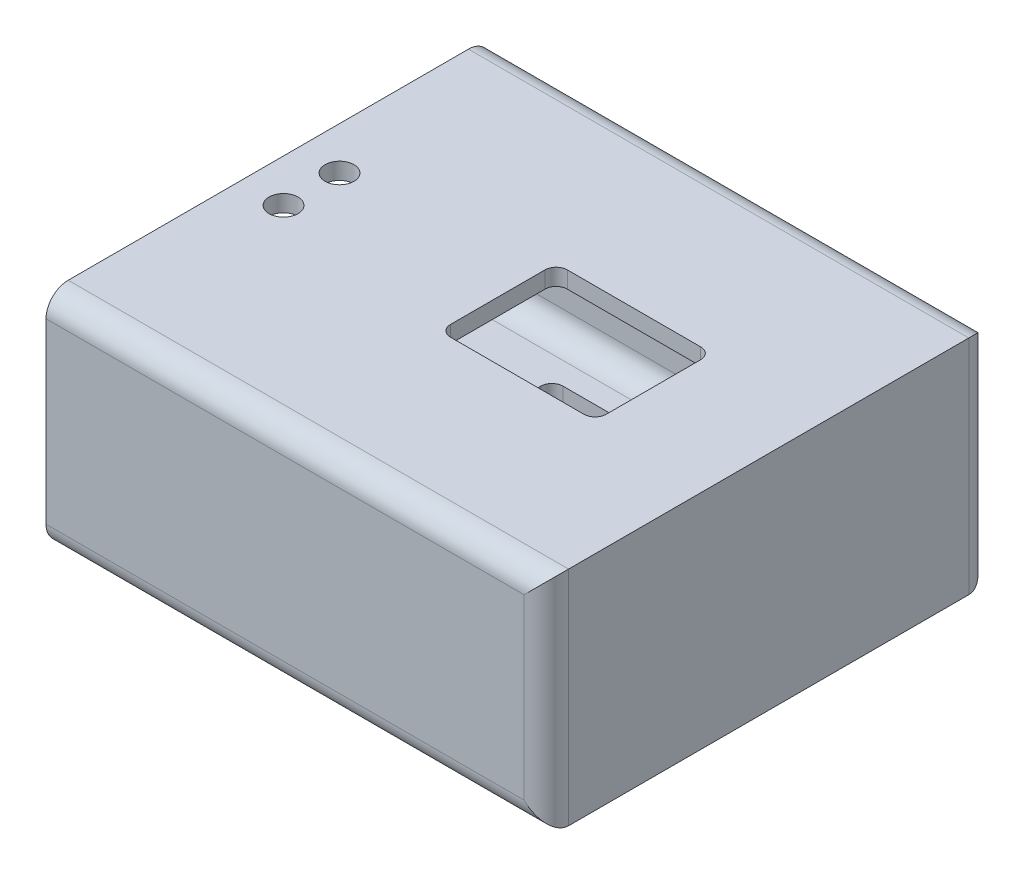
SolidWorks part; units mm, degrees
ref_plane "Front Plane" through (0, 0, 0) normal (0, 0, 1) x (1, 0, 0)
ref_plane "Top Plane" through (0, 0, 0) normal (0, 1, 0) x (1, 0, 0)
ref_plane "Right Plane" through (0, 0, 0) normal (1, 0, 0) x (0, 0, -1)
sketch "Sketch1" plane through (0, 0, 0) normal (1, 0, 0) x (0, 0, -1)
  line L1 (-25.4, -12.7) -> (25.4, -12.7)
  line L2 (-25.4, -12.7) -> (-25.4, 12.7)
  line L3 (-25.4, 12.7) -> (25.4, 12.7)
  line L4 (25.4, -12.7) -> (25.4, 12.7)
  line L5 (-25.4, -12.7) -> (25.4, 12.7) construction
  line L6 (-25.4, 12.7) -> (25.4, -12.7) construction
  point P0 (0, 0)
  dimension "D1" = 50.8
  dimension "D2" = 25.4
extrude "Boss-Extrude1" add sketch "Sketch1" along normal blind 57.15
shell "Shell1" thickness 1.905
sketch "Sketch2" plane through (0, 12.7, 0) normal (0, 1, 0) x (1, 0, 0)
  line L0 (57.15, 25.4) -> (57.15, -25.4) construction
  line L1 (43.9875, 6.6675) -> (26.2075, 6.6675)
  line L2 (43.9875, 6.6675) -> (43.9875, -6.6675)
  line L3 (43.9875, -6.6675) -> (26.2075, -6.6675)
  line L4 (26.2075, 6.6675) -> (26.2075, -6.6675)
  line L5 (43.9875, 6.6675) -> (26.2075, -6.6675) construction
  line L6 (43.9875, -6.6675) -> (26.2075, 6.6675) construction
  point P0 (35.0975, 0)
  point P5 (41.0788, 0)
  point P6 (39.615, 0)
  point P7 (49.3438, 6.0313)
  point P8 (32.9414, -4.3618)
  point P9 (40.4526, 0)
  point P10 (38.9807, 0)
  dimension "D1" = 17.78
  dimension "D2" = 13.335
  dimension "D3" = 13.1625
extrude "Cut-Extrude1" cut sketch "Sketch2" against normal blind 12.7
sketch "Sketch3" plane through (0, -12.7, 0) normal (0, -1, 0) x (1, 0, 0)
  line L0 (57.15, 25.4) -> (57.15, -25.4) construction
  line L1 (13.97, -18.415) -> (45.72, -18.415)
  line L2 (13.97, -18.415) -> (13.97, -8.255)
  line L3 (13.97, -8.255) -> (45.72, -8.255)
  line L4 (45.72, -18.415) -> (45.72, -8.255)
  line L5 (13.97, -18.415) -> (45.72, -8.255) construction
  line L6 (13.97, -8.255) -> (45.72, -18.415) construction
  line L7 (57.15, -25.4) -> (0, -25.4) construction
  point P0 (29.845, -13.335)
  point P5 (34.0795, -13.8686)
  dimension "D1" = 31.75
  dimension "D2" = 10.16
  dimension "D3" = 11.43
  dimension "D4" = 6.985
extrude "Cut-Extrude2" cut sketch "Sketch3" against normal blind 12.7
fillet "Fillet1" radius 2.54 10 edges at (27.6225, -10.795, 23.495) (27.6225, 10.795, 23.495) (27.6225, 10.795, -23.495) (27.6225, -10.795, -23.495) (28.575, 12.7, -25.4) (28.575, -12.7, 25.4) (28.575, -12.7, -25.4) (28.575, 12.7, 25.4) (57.15, 0, -25.4) (57.15, 0, 25.4)
fillet "Fillet2" radius 1.27 4 edges at (26.2075, 11.7475, 6.6675) (43.9875, 11.7475, 6.6675) (43.9875, 11.7475, -6.6675) (26.2075, 11.7475, -6.6675)
fillet "Fillet3" radius 1.27 4 edges at (13.97, -11.7475, -18.415) (45.72, -11.7475, -18.415) (45.72, -11.7475, -8.255) (13.97, -11.7475, -8.255)
sketch "Sketch5" plane through (0, 12.7, 0) normal (0, 1, 0) x (1, 0, 0)
  circle A0 centre (4.8875, 3.2434) radius 1.651
  circle A1 centre (4.8875, -3.1566) radius 1.651
  dimension "D1" = 3.302
  dimension "D2" = 3.302
extrude "Cut-Extrude3" cut sketch "Sketch5" against normal blind 2.54
